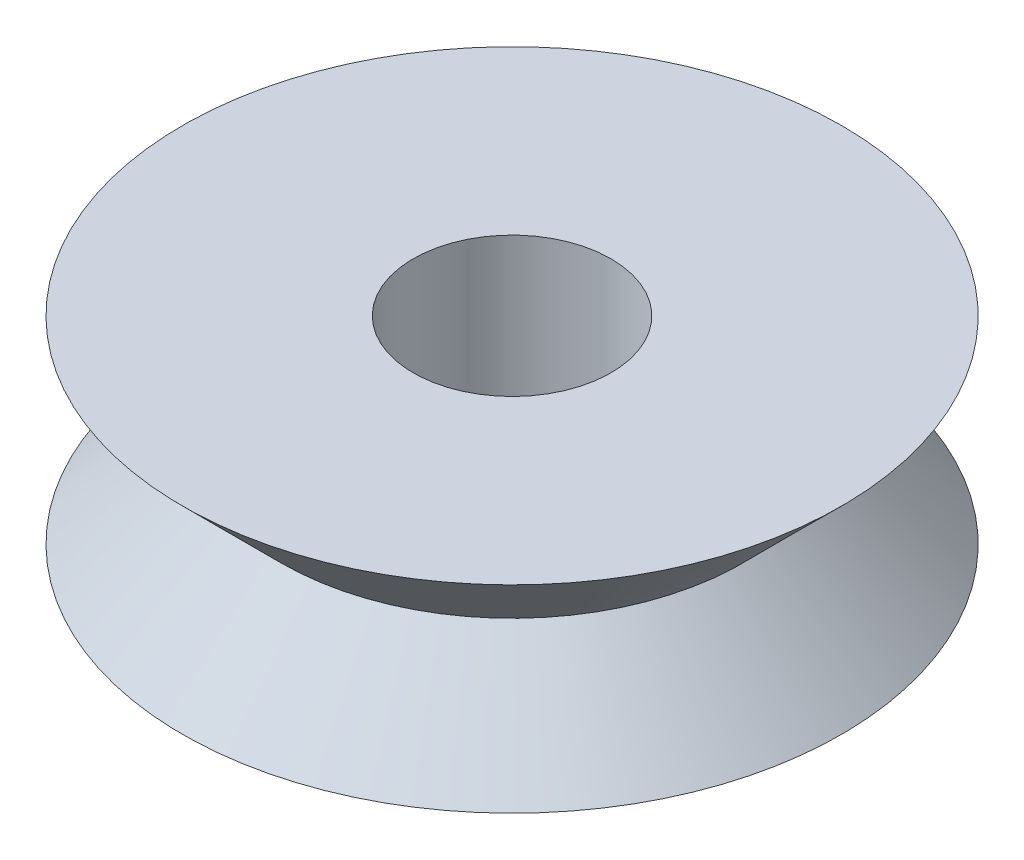
SolidWorks part; units mm, degrees
ref_plane "Front Plane" through (0, 0, 0) normal (0, 0, 1) x (1, 0, 0)
ref_plane "Top Plane" through (0, 0, 0) normal (0, 1, 0) x (1, 0, 0)
ref_plane "Right Plane" through (0, 0, 0) normal (1, 0, 0) x (0, 0, -1)
sketch "Sketch1" plane through (0, 0, 0) normal (0, 0, 1) x (1, 0, 0)
  line L0 (0, 0) -> (0, 6.3059) construction
  line L1 (1.5, 0) -> (5, 0)
  line L2 (5, 0) -> (3.5, 1.5)
  line L3 (3.5, 1.5) -> (5, 3)
  line L4 (5, 3) -> (1.5, 3)
  line L5 (1.5, 3) -> (1.5, 0)
  point P5 (4.858, 0)
  point P9 (0, 0)
  point P10 (0, 0)
  dimension "D1" = 3
  dimension "D2" = 3
  dimension "D3" = 5
revolve "Revolve1" add sketch "Sketch1" angle 360 about L0
